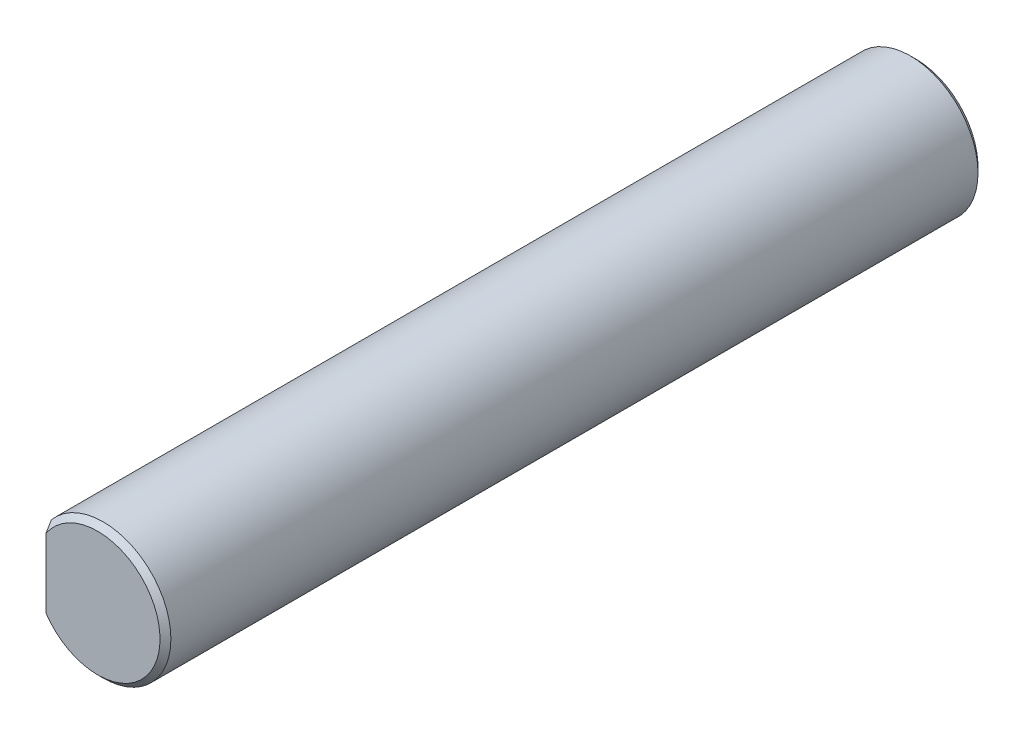
SolidWorks part; units mm, degrees
ref_plane "Front Plane" through (0, 0, 0) normal (0, 0, 1) x (1, 0, 0)
ref_plane "Top Plane" through (0, 0, 0) normal (0, 1, 0) x (1, 0, 0)
ref_plane "Right Plane" through (0, 0, 0) normal (1, 0, 0) x (0, 0, -1)
sketch "Sketch1" plane through (0, 0, 0) normal (0, 0, 1) x (1, 0, 0)
  line L0 (-2.4105, 2.032) -> (-2.4105, -2.032)
  circle A0 centre (0, 0) radius 3.1527
  dimension "D1" = 4.064
  dimension "D2" = 2.4105
extrude "Boss-Extrude1" add sketch "Sketch1" against normal blind 38.1 contours L0 A0
chamfer "Chamfer2" distance 0.254 2 edges at (3.1527, 0, -38.1) (3.1527, 0, 0)
